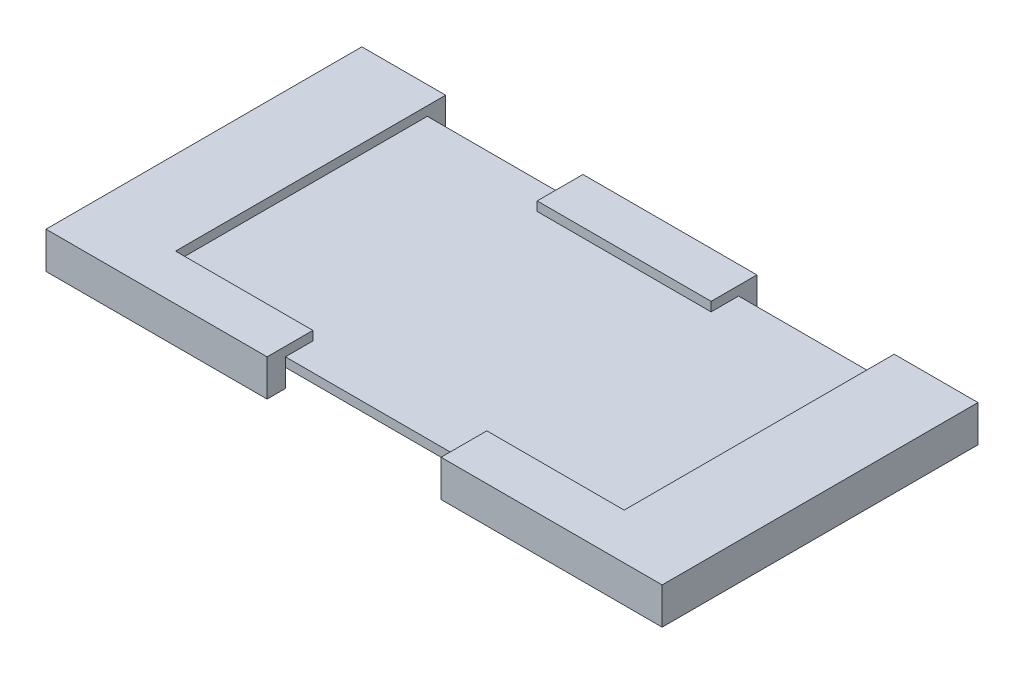
SolidWorks part; units mm, degrees
ref_plane "Front" through (0, 0, 0) normal (0, 0, 1) x (1, 0, 0)
ref_plane "Top" through (0, 0, 0) normal (0, 1, 0) x (1, 0, 0)
ref_plane "Right" through (0, 0, 0) normal (1, 0, 0) x (0, 0, -1)
sketch "Эскиз1" plane through (0, 0, 0) normal (0, 1, 0) x (1, 0, 0)
  line L1 (-33.65, -17.25) -> (33.65, -17.25)
  line L2 (-33.65, -17.25) -> (-33.65, 17.25)
  line L3 (-33.65, 17.25) -> (33.65, 17.25)
  line L4 (33.65, -17.25) -> (33.65, 17.25)
  line L5 (-33.65, -17.25) -> (33.65, 17.25) construction
  line L6 (-33.65, 17.25) -> (33.65, -17.25) construction
  point P0 (0, 0)
  dimension "D1" = 34.5
  dimension "D2" = 67.3
extrude "Бобышка-Вытянуть1" add sketch "Эскиз1" along normal blind 4
sketch "Эскиз2" plane through (0, 4, 0) normal (0, 1, 0) x (1, 0, 0)
  line L0 (33.65, 17.25) -> (-33.65, 17.25) construction
  line L1 (-24.5, 17.25) -> (-9.5, 17.25)
  line L2 (-24.5, 17.25) -> (-24.5, -12.25)
  line L3 (-24.5, -12.25) -> (-9.5, -12.25)
  line L4 (-9.5, 17.25) -> (-9.5, -12.25)
  line L5 (-33.65, -17.25) -> (33.65, -17.25) construction
  line L6 (9.5, 17.25) -> (24.5, 17.25)
  line L7 (9.5, 17.25) -> (9.5, -12.25)
  line L8 (9.5, -12.25) -> (24.5, -12.25)
  line L9 (24.5, 17.25) -> (24.5, -12.25)
  line L14 (-33.65, 17.25) -> (-33.65, -17.25) construction
  line L15 (33.65, -17.25) -> (33.65, 17.25) construction
  dimension "D1" = 9.15
  dimension "D2" = 15
  dimension "D3" = 5
  dimension "D4" = 9.15
extrude "Вырез-Вытянуть1" cut sketch "Эскиз2" against normal blind 1
sketch "Эскиз3" plane through (0, 0, 0) normal (0, -1, 0) x (-1, 0, 0)
  line L0 (-33.65, -17.25) -> (-33.65, 17.25) construction
  line L1 (-31.65, 15.25) -> (31.65, 15.25)
  line L2 (-31.65, 15.25) -> (-31.65, -15.25)
  line L3 (-31.65, -15.25) -> (31.65, -15.25)
  line L4 (31.65, 15.25) -> (31.65, -15.25)
  line L5 (33.65, 17.25) -> (33.65, -17.25) construction
  line L6 (-33.65, 17.25) -> (33.65, 17.25) construction
  line L7 (33.65, -17.25) -> (-33.65, -17.25) construction
  dimension "D1" = 2
  dimension "D2" = 2
  dimension "D3" = 2
  dimension "D4" = 2
extrude "Вырез-Вытянуть2" cut sketch "Эскиз3" against normal blind 2
sketch "Эскиз4" plane through (0, 0, -17.25) normal (0, 0, -1) x (-1, 0, 0)
  line L0 (-33.65, 0) -> (33.65, 0) construction
  line L1 (-24.5, 3) -> (-9.5, 3)
  line L2 (-24.5, 3) -> (-24.5, 0)
  line L3 (-24.5, 0) -> (-9.5, 0)
  line L4 (-9.5, 3) -> (-9.5, 0)
  line L6 (9.5, 3) -> (24.5, 3)
  line L7 (9.5, 3) -> (9.5, 0)
  line L8 (9.5, 0) -> (24.5, 0)
  line L9 (24.5, 3) -> (24.5, 0)
extrude "Вырез-Вытянуть3" cut sketch "Эскиз4" against normal blind 2
sketch "Эскиз6" plane through (0, 4, 0) normal (0, 1, 0) x (1, 0, 0)
  line L0 (-9.5, -12.25) -> (-9.5, 17.25) construction
  line L1 (9.5, -17.25) -> (-9.5, -17.25)
  line L2 (9.5, -17.25) -> (9.5, 12.25)
  line L3 (9.5, 12.25) -> (-9.5, 12.25)
  line L4 (-9.5, -17.25) -> (-9.5, 12.25)
  line L5 (9.5, 17.25) -> (-9.5, 17.25) construction
  line L6 (9.5, 17.25) -> (9.5, -12.25) construction
  line L7 (-33.65, -17.25) -> (33.65, -17.25) construction
  dimension "D1" = 5
extrude "Вырез-Вытянуть5" cut sketch "Эскиз6" against normal blind 1
sketch "Эскиз5" plane through (0, 0, 17.25) normal (0, 0, 1) x (1, 0, 0)
  line L0 (-33.65, 0) -> (33.65, 0) construction
  line L1 (-9.5, 3) -> (9.5, 3)
  line L2 (-9.5, 3) -> (-9.5, 0)
  line L3 (-9.5, 0) -> (9.5, 0)
  line L4 (9.5, 3) -> (9.5, 0)
  point P7 (0, 0)
  point P12 (0, 0)
  point P14 (0, 0)
extrude "Вырез-Вытянуть4" cut sketch "Эскиз5" against normal blind 2
